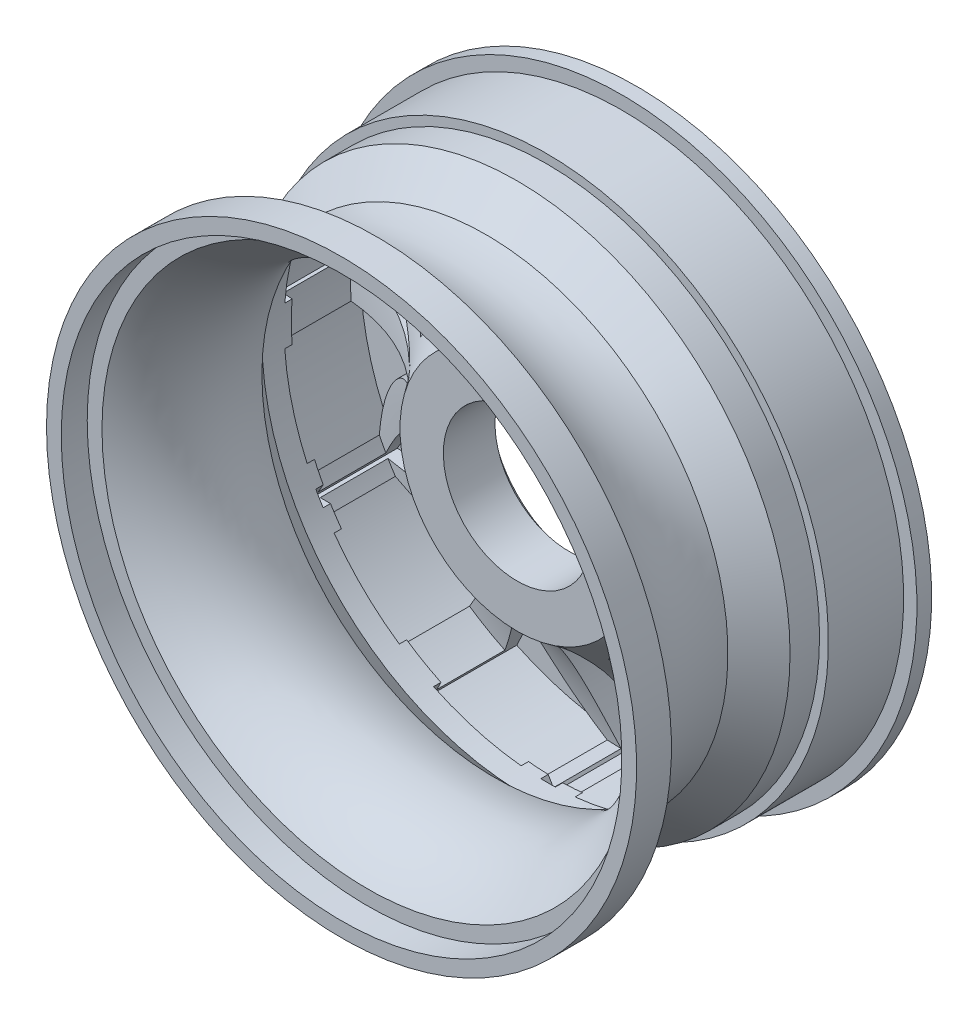
SolidWorks part; units mm, degrees
ref_plane "Ön Düzlem" through (0, 0, 0) normal (0, 0, 1) x (1, 0, 0)
ref_plane "Üst Düzlem" through (0, 0, 0) normal (0, 1, 0) x (1, 0, 0)
ref_plane "Sağ Düzlem" through (0, 0, 0) normal (1, 0, 0) x (0, 0, -1)
sketch "Çizim3" plane through (0, 0, 0) normal (1, 0, 0) x (0, 0, -1)
  line L0 (0, 0) -> (-301.6955, 0) construction
  line L1 (0, 185) -> (0, 200)
  line L2 (0, 200) -> (-10, 200)
  line L3 (-10, 200) -> (-10, 191)
  line L4 (-10, 191) -> (-61, 191)
  line L5 (-61, 191) -> (-61, 185)
  line L6 (-61, 185) -> (-81, 185)
  line L7 (0, 185) -> (-55, 185)
  line L8 (-55, 185) -> (-55, 179)
  line L9 (-55, 179) -> (-75, 179)
  line L10 (-81, 185) -> (-102.0614, 163.9386)
  line L11 (-75, 179) -> (-96.0614, 157.9386)
  line L12 (-176.4, 200) -> (-200, 200)
  line L13 (-200, 200) -> (-200, 190)
  line L14 (-200, 190) -> (-182.4, 190)
  line L15 (-182.4, 190) -> (-182.4, 180)
  line L16 (-176.4, 200) -> (-176.4, 185)
  spline S0 degree 2 poles (-176.4, 185) (-145.5259, 152.8597) (-102.0614, 163.9386) knots 0 0 0 1 1 1
  spline S1 degree 2 poles (-182.4, 180) (-146.3686, 138.9383) (-96.0614, 157.9386) knots 0 0 0 1 1 1
  dimension "D1" = 200
  dimension "D2" = 15
  dimension "D3" = 10
  dimension "D4" = 55
  dimension "D5" = 6
  dimension "D6" = 6
  dimension "D7" = 6
  dimension "D8" = 20
  dimension "D9" = 20
  dimension "D10" = 200
  dimension "D11" = 10
  dimension "D12" = 17.6
  dimension "D13" = 15
  dimension "D14" = 10
  dimension "D15" = 6
revolve "Döndür1" add sketch "Çizim3" angle 360 about L0
sketch "Çizim5" plane through (0, 0, 0) normal (1, 0, 0) x (0, 0, -1)
  line L0 (-81, 79.4) -> (-81, 50)
  line L1 (0, 0) -> (-477.2243, 0) construction
  line L2 (0, 197.3) -> (-7.5, 197.3)
  line L3 (0, -200) -> (0, 200) construction
  line L4 (-81, 185) -> (-81, -185) construction
  line L5 (-81, 50) -> (-46, 50)
  spline S0 degree 2 poles (-81, 79.4) (-14.1232, 122.5201) (-7.5, 197.3) knots 0 0 0 1 1 1
  spline S1 degree 2 poles (-46, 50) (10.0546, 118.5356) (0, 197.3) knots 0 0 0 1 1 1
  point P0 (-477.2243, 0)
  dimension "D1" = 2.7
  dimension "D2" = 7.5
  dimension "D3" = 35
  dimension "D4" = 79.4
  dimension "D5" = 50
revolve "Döndür4" add sketch "Çizim5" angle 360 about L1
sketch "Çizim8" plane through (0, 0, 0) normal (0, 0, 1) x (1, 0, 0)
  line L0 (0, 0) -> (0, -226.2891) construction
  line L1 (0, 0) -> (99.928, -207.5423) construction
  line L2 (0, -77.3) -> (0, -187.3)
  line L3 (28.2907, -58.7575) -> (81.2538, -168.7575)
  circle A0 centre (0, 0) radius 187.3
  spline S0 degree 2 poles (0, -187.3) (35.6262, -131.2321) (0, -77.3) knots 0 0 0 1 1 1
  spline S1 degree 2 poles (28.2907, -58.7575) (71.396, -137.3551) (7.8258, -187.1364) knots 0 0 0 1 1 1
  dimension "D1" = 374.6
  dimension "D2" = 25.71
  dimension "D3" = 110
  dimension "D4" = 110
extrude "Kes-Ekstrüzyon7" cut sketch "Çizim8" along normal blind 60 contours L2 S0 | L3 S1 A0
mirror "Aynalama5" about plane through (0, 0, 0) normal (1, 0, 0) of "Kes-Ekstrüzyon7"
pattern_circular "Dairesel Kaplama6" count 6 over 360 about axis through (0, 0, 0) along (0, 0, -1) of "Aynalama5", "Kes-Ekstrüzyon7"
